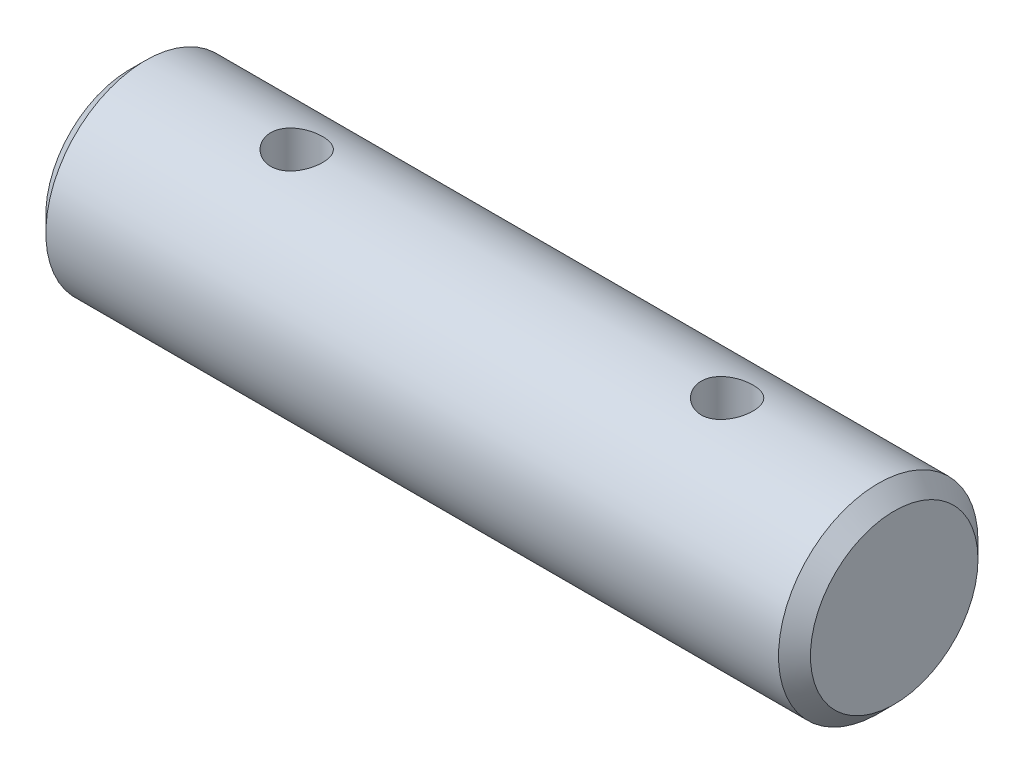
SolidWorks part; units mm, degrees
material "AISI 1045 Aço, trefilado"
ref_plane "Plano frontal" through (0, 0, 0) normal (0, 0, 1) x (1, 0, 0)
ref_plane "Plano superior" through (0, 0, 0) normal (0, 1, 0) x (1, 0, 0)
ref_plane "Plano direito" through (0, 0, 0) normal (1, 0, 0) x (0, 0, -1)
sketch "Esboço1" plane through (0, 0, 0) normal (1, 0, 0) x (0, -1, 0)
  circle A0 centre (0, 0) radius 12.5
  dimension "D1" = 25
extrude "Ressalto-extrusão1" add sketch "Esboço1" along normal mid plane 95.82
chamfer "Chanfro1" distance 2 angle 45 2 edges at (-47.91, 0, -12.5) (47.91, 0, -12.5)
sketch "Esboço2" plane through (0, 0, 0) normal (0, 1, 0) x (1, 0, 0)
  line L0 (-26.97, 0) -> (26.97, 0) construction
  circle A0 centre (-26.97, 0) radius 3.25
  circle A1 centre (26.97, 0) radius 3.25
  dimension "D2" = 6.5
  dimension "D1" = 53.94
extrude "Corte-extrusão1" cut sketch "Esboço2" against normal through all both and the other way through all
